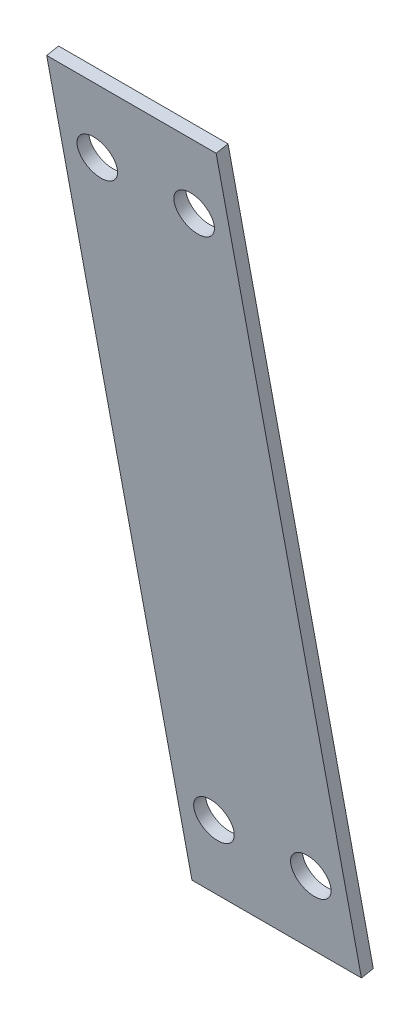
SolidWorks part; units mm, degrees
ref_plane "前视基准面" through (0, 0, 0) normal (0, 0, 1) x (1, 0, 0)
ref_plane "上视基准面" through (0, 0, 0) normal (0, 1, 0) x (1, 0, 0)
ref_plane "右视基准面" through (0, 0, 0) normal (1, 0, 0) x (0, 0, -1)
other "Configuration Table"
sketch "草图1" plane through (0, 0, 0) normal (1, 0, 0) x (0, 0, -1)
  line L0 (0.9834, 40.1815) -> (-23.0166, 170.1815)
  line L1 (-23.0166, 170.1815) -> (-24.9834, 169.8185)
  line L2 (-24.9834, 169.8185) -> (-0.9834, 39.8185)
  line L3 (-0.9834, 39.8185) -> (0.9834, 40.1815)
extrude "Leaf" add sketch "草图1" along normal blind 28 from offset 96
sketch "草图2" plane through (0, 1.1368, -6.1578) normal (0, -0.1815, 0.9834) x (1, 0, 0)
  circle A0 centre (102, 52.3353) radius 3.3
  circle A1 centre (118, 52.3353) radius 3.3
  circle A2 centre (102, 158.5321) radius 3.3
  circle A3 centre (118, 158.5321) radius 3.3
extrude "Mounting Holes" cut sketch "草图2" against normal mid plane 8
